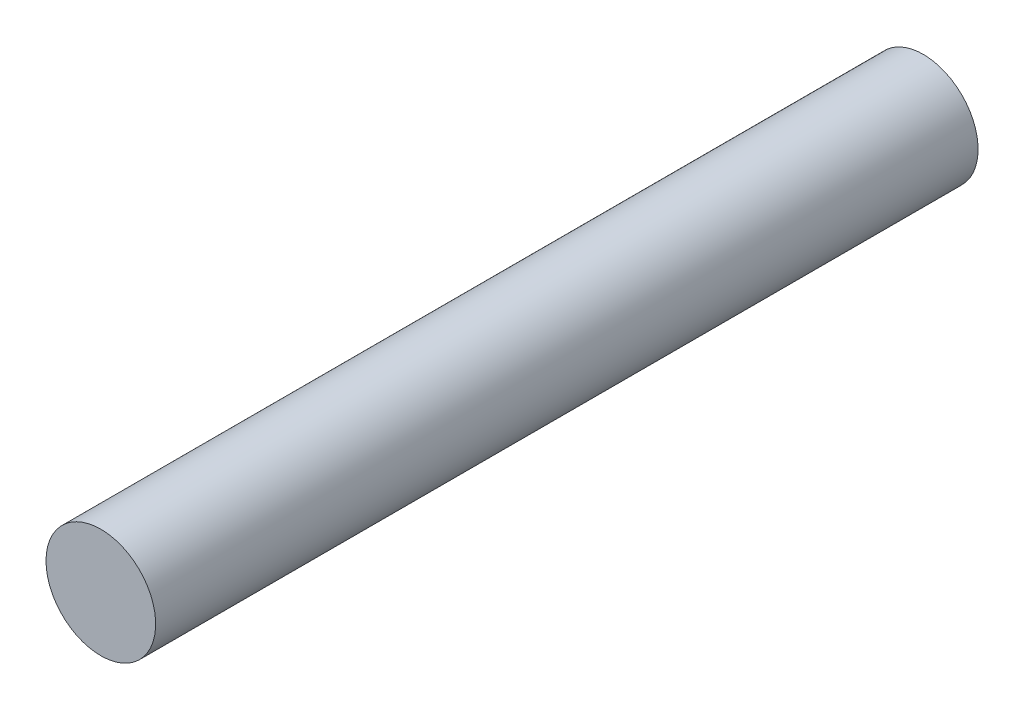
SolidWorks part; units mm, degrees
ref_plane "Front Plane" through (0, 0, 0) normal (0, 0, 1) x (1, 0, 0)
ref_plane "Top Plane" through (0, 0, 0) normal (0, 1, 0) x (1, 0, 0)
ref_plane "Right Plane" through (0, 0, 0) normal (1, 0, 0) x (0, 0, -1)
sketch "Sketch2" plane through (0, 0, 0) normal (0, 0, 1) x (1, 0, 0)
  circle A0 centre (0, 0) radius 6
  dimension "D1" = 12
extrude "Boss-Extrude1" add sketch "Sketch2" along normal blind 90
